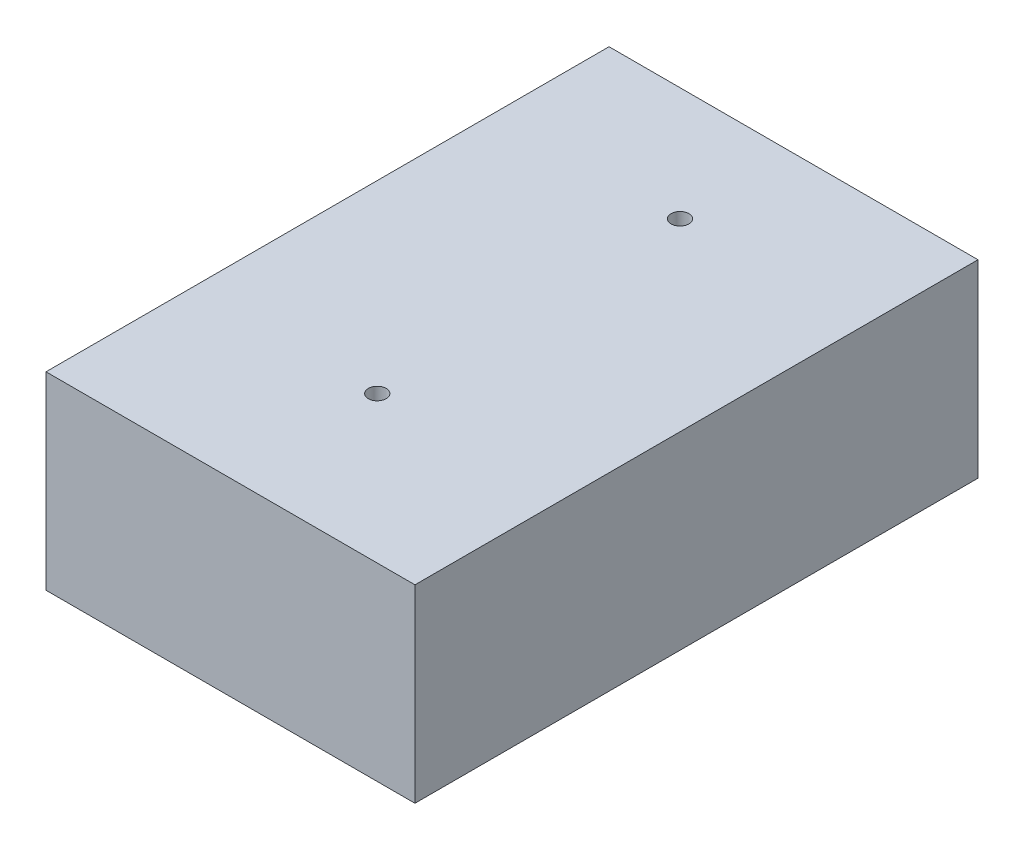
SolidWorks part; units mm, degrees
ref_plane "Front" through (0, 0, 0) normal (0, 0, 1) x (1, 0, 0)
ref_plane "Top" through (0, 0, 0) normal (0, 1, 0) x (1, 0, 0)
ref_plane "Right" through (0, 0, 0) normal (1, 0, 0) x (0, 0, -1)
sketch "Sketch1" plane through (0, 0, 0) normal (0, 1, 0) x (1, 0, 0)
  line L1 (-30.9563, 47.2399) -> (30.9562, 47.2399)
  line L2 (-30.9563, 47.2399) -> (-30.9562, -47.2399)
  line L3 (-30.9562, -47.2399) -> (30.9562, -47.2399)
  line L4 (30.9562, 47.2399) -> (30.9562, -47.2399)
  line L5 (-30.9563, 47.2399) -> (30.9562, -47.2399) construction
  line L6 (-30.9562, -47.2399) -> (30.9562, 47.2399) construction
  point P0 (0, 0)
  dimension "D1" = 61.9125
extrude "Boss-Extrude1" add sketch "Sketch1" along normal blind 31.75
sketch "Sketch2" plane through (0, 31.75, 0) normal (0, 1, 0) x (1, 0, 0)
  line L0 (0, -17.4625) -> (0, 17.4625) construction
  line L1 (30.9562, 47.2399) -> (-30.9563, 47.2399) construction
  circle A0 centre (0, 28.1899) radius 1.5
  circle A1 centre (0, -22.6101) radius 1.5
  dimension "D1" = 3
  dimension "D3" = 3
  dimension "D2" = 19.05
  dimension "D4" = 50.8
extrude "Cut-Extrude1" cut sketch "Sketch2" against normal blind 2.54
